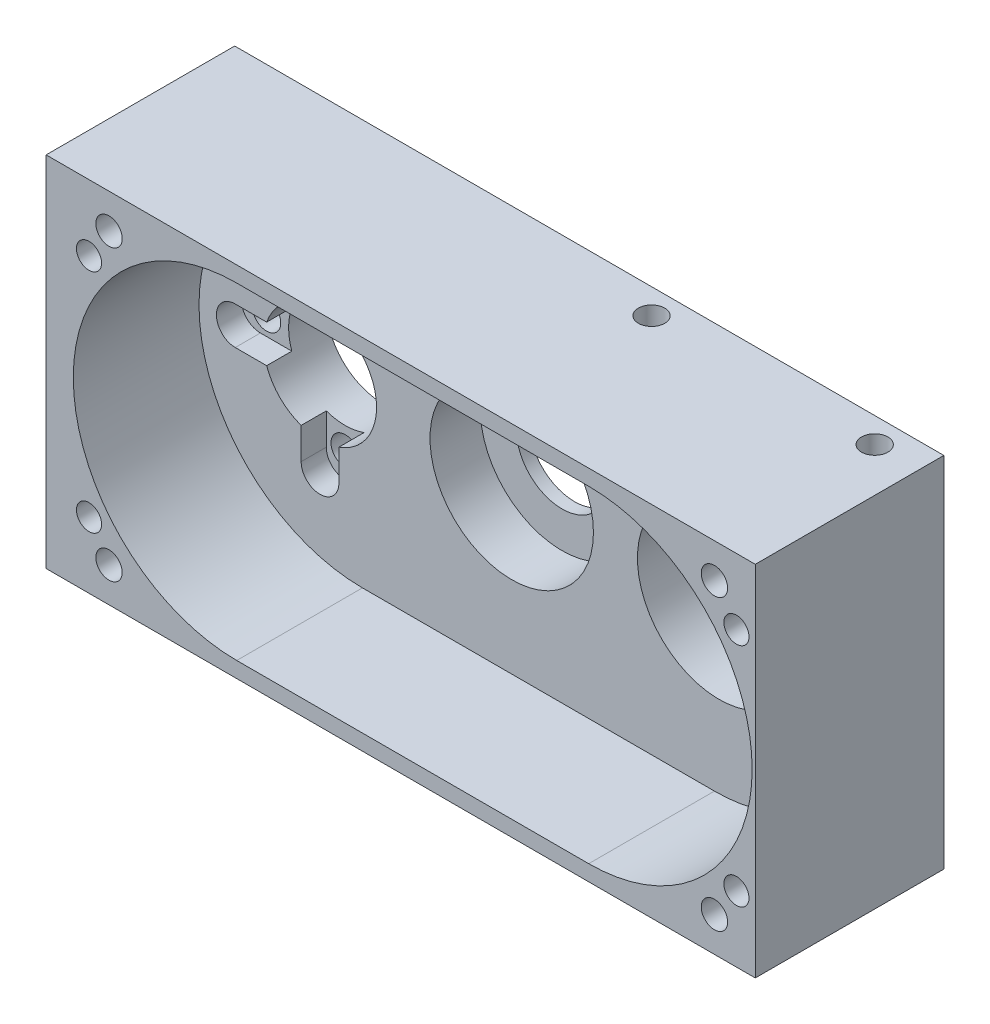
SolidWorks part; units mm, degrees
material "7075-T6, Chapa (SS)"
ref_plane "Plano frontal" through (0, 0, 0) normal (0, 0, 1) x (1, 0, 0)
ref_plane "Plano superior" through (0, 0, 0) normal (0, 1, 0) x (1, 0, 0)
ref_plane "Plano direito" through (0, 0, 0) normal (1, 0, 0) x (0, 0, -1)
sketch "Esboço1" plane through (0, 0, 0) normal (0, 0, 1) x (1, 0, 0)
  line L0 (-54.75, 26) -> (63.25, 26) construction
  line L1 (-54.75, -31) -> (63.25, -31)
  line L2 (-54.75, -31) -> (-54.75, 31)
  line L3 (-54.75, 31) -> (63.25, 31)
  line L4 (63.25, -31) -> (63.25, 31)
  circle A0 centre (0, 0) radius 12 construction
  circle A1 centre (0, 0) radius 10.5 construction
  circle A2 centre (0, 0) radius 23 construction
  circle A3 centre (0, 0) radius 24 construction
  circle A4 centre (33, 0) radius 24 construction
  circle A5 centre (33, 0) radius 22.5 construction
  circle A6 centre (-30.5, 0) radius 7.5 construction
  circle A7 centre (-30.5, 0) radius 8.5 construction
  circle A8 centre (-30.5, 0) radius 17 construction
  circle A9 centre (-30.5, 15) radius 2
  circle A10 centre (-30.5, -15) radius 2
  circle A11 centre (-45.5, 0) radius 2
  circle A12 centre (-30.5, 0) radius 15 construction
  circle A13 centre (-45.5, 0) radius 3 construction
  circle A14 centre (-23.75, 0) radius 26 construction
  circle A15 centre (32.25, 0) radius 26 construction
  point P24 (57, 0)
  point P25 (-47.5, 0)
  point P26 (0, -24)
  point P27 (0, 24)
  point P28 (-48.5, 0)
  point P30 (-49.75, 0)
  point P35 (58.25, 0)
  dimension "D1" = 48
  dimension "D2" = 46
  dimension "D3" = 24
  dimension "D4" = 21
  dimension "D5" = 45
  dimension "D6" = 48
  dimension "D7" = 15
  dimension "D8" = 17
  dimension "D11" = 15
  dimension "D12" = 4
  dimension "D15" = 6
  dimension "D18" = 1.25
  dimension "D9" = 5
  dimension "D10" = 7
  dimension "D13" = 7
  dimension "D14" = 5
  dimension "D16" = 1.25
  dimension "D17" = 5
extrude "Ressalto-extrusão1" add sketch "Esboço1" along normal blind 30 contours L3 L4 L1 L2
sketch "Esboço2" plane through (0, 0, 30) normal (0, 0, 1) x (1, 0, 0)
  line L0 (-23.75, 26) -> (32.25, 26)
  line L1 (-23.75, -26) -> (32.25, -26)
  line L4 (-54.75, 31) -> (63.25, 31) construction
  arc A2 (-23.75, 26) -> (-23.75, -26) centre (-23.75, 0) ccw
  arc A4 (32.25, -26) -> (32.25, 26) centre (32.25, 0) ccw
  dimension "D1" = 5
extrude "Corte-extrusão1" cut sketch "Esboço2" against normal blind 20
sketch "Esboço3" plane through (0, 0, 10) normal (0, 0, 1) x (1, 0, 0)
  line L1 (51, 18.0121) -> (51, -18.0121)
  circle A3 centre (32.25, 0) radius 26 construction
  arc A4 (51, 18.0121) -> (51, -18.0121) centre (32.25, 0) cw
  dimension "D1" = 18
extrude "Ressalto-extrusão2" add sketch "Esboço3" along normal blind 8
sketch "Esboço4" plane through (0, 0, 10) normal (0, 0, 1) x (1, 0, 0)
  circle A0 centre (-30.5, 0) radius 9
  circle A1 centre (0, 0) radius 13
  circle A2 centre (33, 0) radius 13
  dimension "D1" = 26
  dimension "D2" = 18
extrude "Corte-extrusão2" cut sketch "Esboço4" against normal blind 8
sketch "Esboço5" plane through (0, 0, 30) normal (0, 0, 1) x (1, 0, 0)
  line L0 (-54.75, -31) -> (63.25, -31) construction
  line L1 (-54.75, -31) -> (-54.75, 31) construction
  line L2 (-54.75, 31) -> (63.25, 31) construction
  line L3 (63.25, -31) -> (63.25, 31) construction
  circle A0 centre (-47.25, 18) radius 2
  circle A1 centre (55.75, 18) radius 2
  circle A2 centre (55.75, -18) radius 2
  circle A3 centre (-47.25, -18) radius 2
  dimension "D1" = 4
  dimension "D2" = 13
  dimension "D3" = 7.5
  dimension "D5" = 7.5
  dimension "D6" = 13
extrude "Corte-extrusão3" cut sketch "Esboço5" against normal blind 8
sketch "Esboço6" plane through (0, 0, 10) normal (0, 0, 1) x (1, 0, 0)
  line L0 (-38.9853, 3) -> (-43.9853, 3)
  line L1 (-33.5, 8.4853) -> (-27.5, 8.4853)
  line L2 (-33.5, 8.4853) -> (-33.5, 13.4853)
  line L4 (-27.5, 8.4853) -> (-27.5, 13.4853)
  line L12 (-38.9853, -3) -> (-38.9853, 3)
  line L13 (-38.9853, -3) -> (-43.9853, -3)
  line L14 (-33.5, -8.4853) -> (-33.5, -13.4853)
  line L15 (-27.5, -8.4853) -> (-33.5, -8.4853)
  line L16 (-27.5, -8.4853) -> (-27.5, -13.4853)
  line L17 (-30.5, 0) -> (-27.5, 8.4853) construction
  line L18 (-30.5, 0) -> (-38.9853, 3) construction
  arc A3 (-33.5, 13.4853) -> (-27.5, 13.4853) centre (-30.5, 13.4853) cw
  arc A4 (-43.9853, -3) -> (-43.9853, 3) centre (-43.9853, 0) cw
  arc A5 (-27.5, -13.4853) -> (-33.5, -13.4853) centre (-30.5, -13.4853) cw
  circle A6 centre (-30.5, 0) radius 9 construction
  dimension "D1" = 3
  dimension "D2" = 5
  dimension "D3" = 6
  dimension "D4" = 3
  dimension "D5" = 90
  dimension "D6" = 5
extrude "Corte-extrusão4" cut sketch "Esboço6" against normal blind 4
hole_wizard "Broca de rosquear para tarraxa de M52" positions "Esboço7" profile "Esboço8" hole size "M5" standard "ISO"
sketch "Esboço7" plane through (0, 0, 30) normal (0, 0, 1) x (1, 0, 0)
  line L0 (-54.75, 31) -> (63.25, 31) construction
  line L1 (-54.75, -31) -> (-54.75, 31) construction
  line L2 (-54.75, -31) -> (63.25, -31) construction
  line L3 (63.25, -31) -> (63.25, 31) construction
  point P0 (-44.07, 23)
  point P2 (-44.07, -23)
  point P4 (52.25, -23)
  point P6 (52.25, 23)
  dimension "D1" = 8
  dimension "D2" = 10.68
  dimension "D3" = 8
  dimension "D4" = 11
sketch "Esboço8" plane through (-44.07, 23, 30) normal (1, 0, 0) x (0, -1, 0)
  line L0 (0, 0) -> (0, 14.2618)
  line L1 (0, 14.2618) -> (2.1, 13)
  line L2 (2.1, 13) -> (2.1, 0)
  line L5 (2.1, 0) -> (0, 0)
  line L10 (0, 14.2618) -> (-2.1, 13) construction
  line L11 (0, -6.35) -> (0, 107.95) construction
  dimension "Hole Dia." = 4.2
  dimension "Hole Depth" = 13
  dimension "Drill Angle" = 118
hole_wizard "Furo com folga de M41" positions "Esboço16" profile "Esboço15" hole size "M4" standard "Ansi Metric" end condition through all
sketch "Esboço16" plane through (0, 0, 6) normal (0, 0, 1) x (1, 0, 0)
  circle A0 centre (-30.5, 0) radius 12.5 construction
  arc A2 (-38.9853, -3) -> (-33.5, -8.4853) centre (-30.5, 0) ccw construction
  point P8 (-43, 0)
  point P10 (-30.5, 12.5)
  point P12 (-30.5, -12.5)
  dimension "D1" = 25
sketch "Esboço15" plane through (-30.5, -12.5, 6) normal (1, 0, 0) x (0, -1, 0)
  line L0 (0, 0) -> (0, 6)
  line L1 (0, 6) -> (2.25, 6)
  line L2 (2.25, 6) -> (2.25, 0)
  line L5 (2.25, 0) -> (0, 0)
  line L11 (0, -6.35) -> (0, 107.95) construction
  dimension "Thru Hole Dia." = 4.5
  dimension "Thru Hole Depth" = 6
sketch "Esboço17" plane through (0, 0, 30) normal (0, 0, 1) x (1, 0, 0)
  line L1 (63.25, 31) -> (63.25, -31)
  line L2 (63.25, -31) -> (-54.75, -31)
  line L3 (-54.75, -31) -> (-54.75, 31)
  line L5 (58.75, 28.5) -> (58.75, -28.5)
  line L6 (58.75, -28.5) -> (-54.07, -28.5)
  line L7 (-54.07, -28.5) -> (-54.07, 28.5)
  line L10 (63.25, 31) -> (-54.75, 31)
  line L13 (-54.07, 28.5) -> (58.75, 28.5)
  dimension "D1" = 0.68
  dimension "D2" = 4.5
  dimension "D3" = 2.5
  dimension "D4" = 2.5
extrude "Corte-extrusão5" cut sketch "Esboço17" against normal through all
hole_wizard "Broca de rosquear para tarraxa de M54" positions "Esboço22" profile "Esboço21" hole size "M5" standard "ISO"
sketch "Esboço22" plane through (0, -28.5, 0) normal (0, -1, 0) x (-1, 0, 0)
  line L3 (-58.75, 0) -> (-58.75, -30) construction
  line L5 (-58.75, -4) -> (-16.25, -4) construction
  line L7 (54.07, 0) -> (-58.75, 0) construction
  point P0 (-51.75, -4)
  point P2 (-16.25, -4)
  dimension "D1" = 4
  dimension "D2" = 7
  dimension "D3" = 35.5
sketch "Esboço21" plane through (51.75, -28.5, 4) normal (1, 0, 0) x (0, 0, -1)
  line L0 (0, 0) -> (0, 16.2618)
  line L1 (0, 16.2618) -> (2.1, 15)
  line L2 (2.1, 15) -> (2.1, 0)
  line L5 (2.1, 0) -> (0, 0)
  line L10 (0, 16.2618) -> (-2.1, 15) construction
  line L11 (0, -6.35) -> (0, 107.95) construction
  dimension "Hole Dia." = 4.2
  dimension "Hole Depth" = 15
  dimension "Drill Angle" = 118
hole_wizard "Broca de rosquear para tarraxa de M55" positions "Esboço23" profile "Esboço24" hole size "M5" standard "ISO"
sketch "Esboço23" plane through (0, 28.5, 0) normal (0, 1, 0) x (1, 0, 0)
  line L0 (58.75, 0) -> (58.75, -30) construction
  line L1 (58.75, 0) -> (-54.07, 0) construction
  line L2 (51.75, -4) -> (16.25, -4) construction
  point P0 (51.75, -4)
  point P2 (16.25, -4)
  dimension "D1" = 7
  dimension "D2" = 4
  dimension "D3" = 35.5
sketch "Esboço24" plane through (51.75, 28.5, 4) normal (1, 0, 0) x (0, 0, 1)
  line L0 (0, 0) -> (0, 16.2618)
  line L1 (0, 16.2618) -> (2.1, 15)
  line L2 (2.1, 15) -> (2.1, 0)
  line L5 (2.1, 0) -> (0, 0)
  line L10 (0, 16.2618) -> (-2.1, 15) construction
  line L11 (0, -6.35) -> (0, 107.95) construction
  dimension "Hole Dia." = 4.2
  dimension "Hole Depth" = 15
  dimension "Drill Angle" = 118
sketch "Esboço25" plane through (0, 0, 10) normal (0, 0, 1) x (1, 0, 0)
  circle A0 centre (-30.5, 0) radius 9
  dimension "D1" = 18
extrude "Corte-extrusão6" cut sketch "Esboço25" against normal through all
hole_wizard "Broca de rosquear para tarraxa de M56" positions "Esboço26" profile "Esboço27" hole size "M5" standard "ISO"
sketch "Esboço26" plane through (0, 0, 0) normal (0, 0, -1) x (-1, 0, 0)
  line L0 (54.07, 28.5) -> (54.07, -28.5) construction
  line L1 (-58.75, 28.5) -> (54.07, 28.5) construction
  line L2 (54.07, -28.5) -> (-58.75, -28.5) construction
  point P0 (47.123, 21.276)
  point P2 (47.123, -21.276)
  point P4 (13.877, -21.28)
  point P6 (13.877, 21.28)
  dimension "D1" = 6.947
  dimension "D2" = 6.947
  dimension "D3" = 7.224
  dimension "D4" = 7.224
  dimension "D5" = 7.22
  dimension "D6" = 7.22
  dimension "D7" = 40.193
  dimension "D8" = 40.193
sketch "Esboço27" plane through (-47.123, 21.276, 0) normal (1, 0, 0) x (0, 1, 0)
  line L0 (0, 0) -> (0, 9.2618)
  line L1 (0, 9.2618) -> (2.1, 8)
  line L2 (2.1, 8) -> (2.1, 0)
  line L5 (2.1, 0) -> (0, 0)
  line L10 (0, 9.2618) -> (-2.1, 8) construction
  line L11 (0, -6.35) -> (0, 107.95) construction
  dimension "Hole Dia." = 4.2
  dimension "Hole Depth" = 8
  dimension "Drill Angle" = 118
hole_wizard "Furo com folga de M51" positions "Esboço28" profile "Esboço29" hole size "M5" standard "ISO" end condition through all
sketch "Esboço28" plane through (0, 0, 2) normal (0, 0, 1) x (1, 0, 0)
  point P0 (33, 0)
sketch "Esboço29" plane through (33, 0, 2) normal (1, 0, 0) x (0, -1, 0)
  line L0 (0, 0) -> (0, 2)
  line L1 (0, 2) -> (2.75, 2)
  line L2 (2.75, 2) -> (2.75, 0)
  line L5 (2.75, 0) -> (0, 0)
  line L11 (0, -6.35) -> (0, 107.95) construction
  dimension "Thru Hole Dia." = 5.5
  dimension "Thru Hole Depth" = 2
sketch "Esboço30" plane through (0, 0, 2) normal (0, 0, 1) x (1, 0, 0)
  circle A0 centre (0, 0) radius 7.25
  dimension "D1" = 14.5
extrude "Corte-extrusão9" cut sketch "Esboço30" against normal blind 10 contours A0
